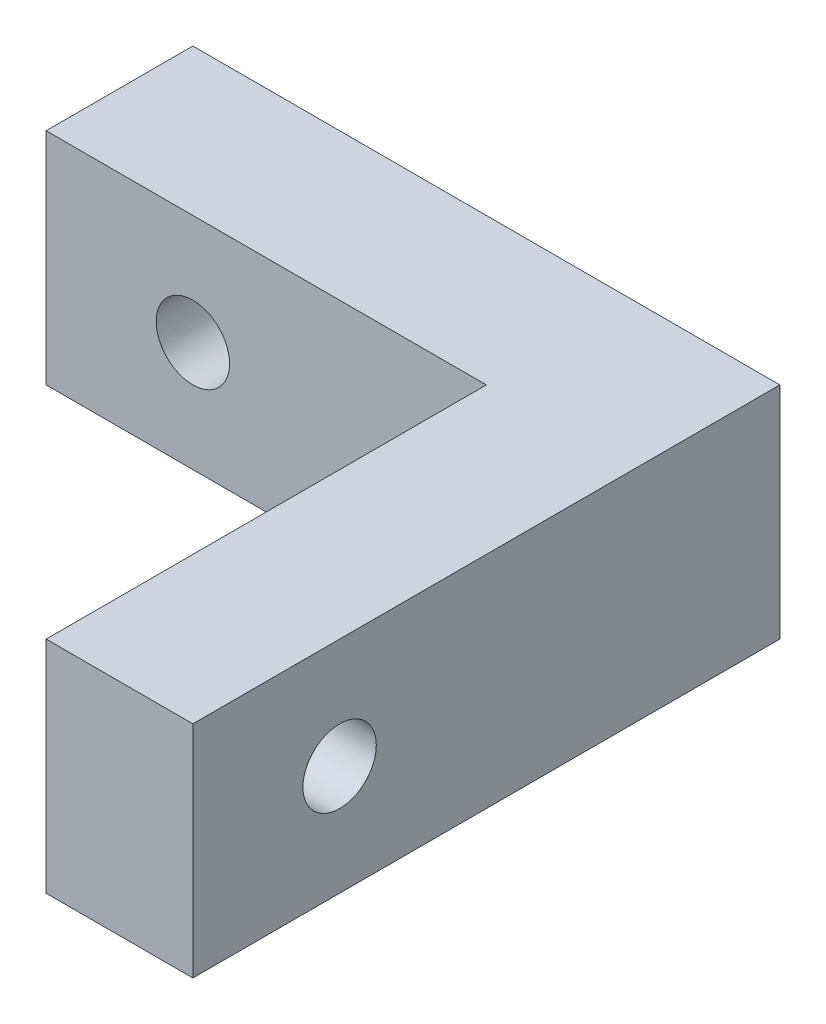
SolidWorks part; units mm, degrees
ref_plane "Front Plane" through (0, 0, 0) normal (0, 0, 1) x (1, 0, 0)
ref_plane "Top Plane" through (0, 0, 0) normal (0, 1, 0) x (1, 0, 0)
ref_plane "Right Plane" through (0, 0, 0) normal (1, 0, 0) x (0, 0, -1)
sketch "Sketch1" plane through (0, 0, 0) normal (0, 0, 1) x (1, 0, 0)
  line L0 (-40, 15) -> (-20, 15)
  line L1 (-40, 15) -> (40, 15)
  line L2 (-40, 15) -> (-40, -15)
  line L3 (-40, -15) -> (40, -15)
  line L4 (40, 15) -> (40, -15)
  line L5 (-40, 15) -> (40, -15) construction
  line L6 (-40, -15) -> (40, 15) construction
  line L7 (-40, 0) -> (-20, 0) construction
  circle A0 centre (-20, 0) radius 5
  point P0 (0, 0)
  dimension "D3" = 10
  dimension "D1" = 80
  dimension "D2" = 30
extrude "Boss-Extrude1" add sketch "Sketch1" along normal blind 20 contours L4 L1 L0 L2 L3 A0
sketch "Sketch2" plane through (0, 0, 20) normal (0, 0, 1) x (1, 0, 0)
  line L0 (40, 15) -> (20, 15)
  line L1 (40, 15) -> (40, -15) construction
  line L2 (-40, 15) -> (40, 15) construction
  line L3 (20, 15) -> (20, -15)
  line L4 (-40, -15) -> (40, -15) construction
  line L5 (20, -15) -> (40, -15)
  line L6 (40, -15) -> (40, 15)
extrude "Boss-Extrude2" add sketch "Sketch2" along normal blind 60
sketch "Sketch3" plane through (20, 0, 0) normal (-1, 0, 0) x (0, 0, 1)
  circle A0 centre (60, 0) radius 5
extrude "Cut-Extrude1" cut sketch "Sketch3" against normal blind 60
